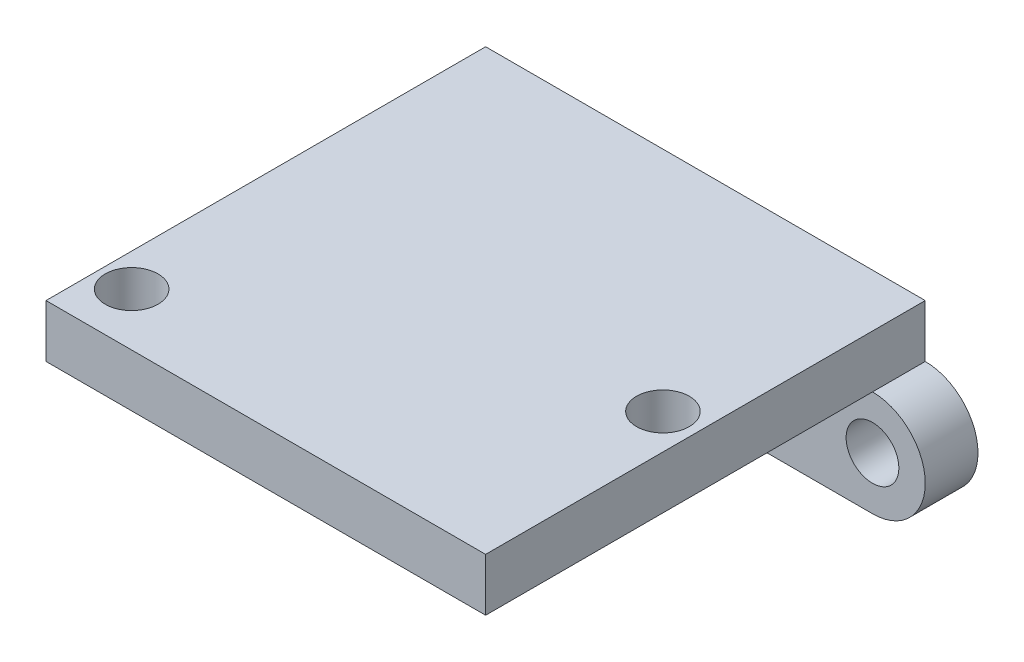
SolidWorks part; units mm, degrees
ref_plane "前视基准面" through (0, 0, 0) normal (0, 0, 1) x (1, 0, 0)
ref_plane "上视基准面" through (0, 0, 0) normal (0, 1, 0) x (1, 0, 0)
ref_plane "右视基准面" through (0, 0, 0) normal (1, 0, 0) x (0, 0, -1)
sketch "草图1" plane through (0, 0, 0) normal (0, 0, 1) x (1, 0, 0)
  line L0 (12.5, 0) -> (-12.5, 0) construction
  line L1 (12.5, 3) -> (-12.5, 3)
  line L2 (12.5, -3) -> (-12.5, -3)
  circle A0 centre (-12.5, 0) radius 1.5
  circle A1 centre (12.5, 0) radius 1.5
  circle A2 centre (-12.5, 0) radius 3
  circle A3 centre (12.5, 0) radius 3
  point P4 (0, 0)
  dimension "D2" = 3
  dimension "D1" = 25
  dimension "D3" = 3
  dimension "D4" = 3
extrude "凸台-拉伸1" add sketch "草图1" along normal blind 3
sketch "草图2" plane through (0, 0, 3) normal (0, 0, 1) x (1, 0, 0)
  line L5 (12.5, 3) -> (-12.5, 3) construction
  line L6 (-12.5, 6) -> (12.5, 6)
  line L7 (-12.5, 6) -> (-12.5, 3)
  line L8 (-12.5, 3) -> (12.5, 3)
  line L9 (12.5, 6) -> (12.5, 3)
  line L10 (-12.5, 6) -> (12.5, 3) construction
  line L11 (-12.5, 3) -> (12.5, 6) construction
  circle A1 centre (-12.5, 0) radius 1.5 construction
  point P0 (0, 4.5)
  dimension "D1" = 3
  dimension "D2" = 0
extrude "凸台-拉伸2" add sketch "草图2" along normal blind 25 from surface at -3 starting at face at (0, 0, 0)
sketch "草图8" plane through (0, 3, 0) normal (0, -1, 0) x (1, 0, 0)
  line L0 (-10.6294, 22) -> (10.5025, 12.9202) construction
  line L1 (-12.5, 25) -> (12.5, 25) construction
  circle A0 centre (-10.6294, 22) radius 1.5
  circle A1 centre (10.5025, 12.9202) radius 1.5
  dimension "D2" = 3
  dimension "D1" = 23
  dimension "D3" = 23.252
  dimension "D4" = 3
extrude "切除-拉伸1" cut sketch "草图8" against normal through all
